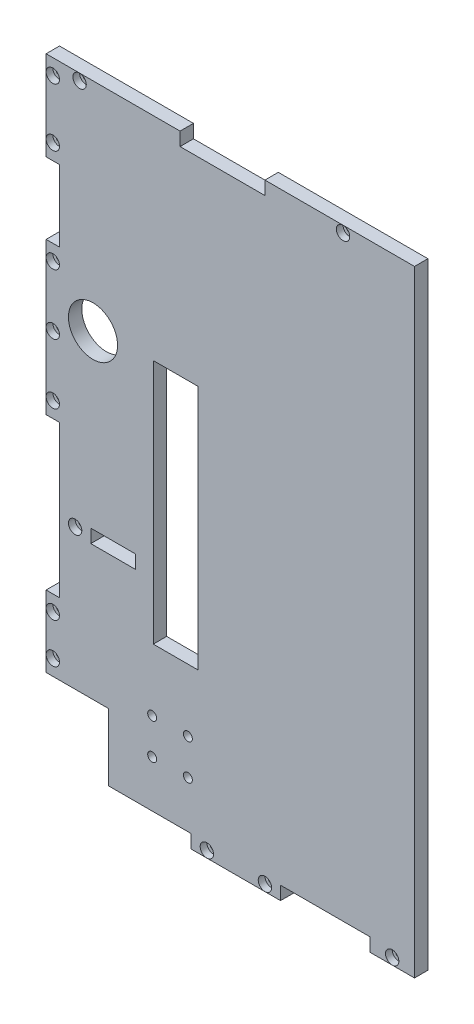
SolidWorks part; units mm, degrees
ref_plane "Plan de face" through (0, 0, 0) normal (0, 0, 1) x (1, 0, 0)
ref_plane "Plan de dessus" through (0, 0, 0) normal (0, 1, 0) x (1, 0, 0)
ref_plane "Plan de droite" through (0, 0, 0) normal (1, 0, 0) x (0, 0, -1)
sketch "Esquisse1" plane through (0, 0, 0) normal (0, 0, 1) x (1, 0, 0)
  line L1 (0, 0) -> (-165, 0)
  line L2 (0, 0) -> (0, 276)
  line L3 (0, 276) -> (-165, 276)
  line L4 (-165, 0) -> (-165, 276)
  dimension "D1" = 276
  dimension "D2" = 165
extrude "Boss.-Extru.1" add sketch "Esquisse1" along normal blind 6
sketch "Esquisse2" plane through (0, 0, 6) normal (0, 0, 1) x (1, 0, 0)
  line L8 (0, 276) -> (-165, 276) construction
  line L9 (-165, 0) -> (0, 0) construction
  line L10 (-105, 276) -> (-67, 276)
  line L11 (-105, 276) -> (-105, 270)
  line L12 (-105, 270) -> (-67, 270)
  line L13 (-165, 276) -> (-165, 0) construction
  line L14 (-165, 236) -> (-159, 236)
  line L15 (-165, 236) -> (-165, 204)
  line L16 (-165, 204) -> (-159, 204)
  line L17 (-159, 236) -> (-159, 204)
  line L19 (-165, 136) -> (-159, 136)
  line L20 (-165, 136) -> (-165, 68)
  line L21 (-165, 68) -> (-159, 68)
  line L22 (-159, 136) -> (-159, 68)
  line L23 (-137, 36) -> (-137, 6)
  line L24 (-165, 0) -> (-165, 36)
  line L25 (-165, 36) -> (-137, 36)
  line L26 (-100, 0) -> (-165, 0)
  line L27 (-20, 0) -> (-60, 0)
  line L28 (-20, 0) -> (-20, 6)
  line L29 (-20, 6) -> (-60, 6)
  line L30 (-60, 0) -> (-60, 6)
  line L31 (0, 0) -> (0, 276) construction
  line L33 (-100, 0) -> (-100, 6)
  line L34 (-100, 6) -> (-137, 6)
  line L35 (-67, 276) -> (-67, 270)
  dimension "D1" = 6
  dimension "D2" = 6
  dimension "D3" = 68
  dimension "D4" = 32
  dimension "D5" = 40
  dimension "D6" = 68
  dimension "D7" = 36
  dimension "D8" = 28
  dimension "D9" = 6
  dimension "D10" = 40
  dimension "D11" = 6
  dimension "D12" = 40
  dimension "D13" = 20
  dimension "D14" = 38
  dimension "D15" = 60
  dimension "D16" = 6
extrude "exterieur" cut sketch "Esquisse2" against normal blind 10
sketch "Esquisse3" plane through (0, 0, 6) normal (0, 0, 1) x (1, 0, 0)
  line L0 (-165, 204) -> (-159, 204) construction
  line L1 (-145, 102) -> (-125, 102)
  line L2 (-145, 102) -> (-145, 96)
  line L3 (-145, 96) -> (-125, 96)
  line L4 (-125, 102) -> (-125, 96)
  line L5 (-165, 204) -> (-165, 136) construction
  line L6 (-165, 68) -> (-165, 36) construction
  line L8 (-100, 0) -> (-60, 0) construction
  circle A0 centre (-144, 178.92) radius 11
  dimension "D1" = 22
  dimension "D2" = 20
  dimension "D4" = 21
  dimension "D3" = 6
  dimension "D5" = 25.08
  dimension "D6" = 20
  dimension "D7" = 102
extrude "Enlèv. mat.-Extru.2" cut sketch "Esquisse3" against normal through all
sketch "Esquisse4" plane through (0, 0, 6) normal (0, 0, 1) x (1, 0, 0)
  line L0 (-105, 270) -> (-67, 270) construction
  line L1 (-145, 96) -> (-125, 96) construction
  line L2 (-105, 276) -> (-105, 270) construction
  line L3 (-67, 270) -> (-67, 276) construction
  line L4 (-165, 204) -> (-159, 204) construction
  line L5 (-159, 136) -> (-165, 136) construction
  line L6 (-165, 68) -> (-159, 68) construction
  line L7 (-137, 36) -> (-165, 36) construction
  line L8 (-100, 0) -> (-100, 6) construction
  line L9 (-60, 6) -> (-60, 0) construction
  line L10 (-100, 0) -> (-60, 0) construction
  line L11 (-165, 68) -> (-165, 36) construction
  line L12 (-165, 204) -> (-165, 136) construction
  line L13 (-20, 0) -> (0, 0) construction
  line L14 (-20, 0) -> (-20, 6) construction
  line L15 (-145, 102) -> (-145, 96) construction
  line L17 (-159, 236) -> (-165, 236) construction
  line L18 (-105, 276) -> (-165, 276) construction
  line L19 (-165, 276) -> (-165, 236) construction
  circle A0 centre (-32, 273) radius 1.5
  circle A1 centre (-150, 273) radius 1.5
  circle A2 centre (-162, 197) radius 1.5
  circle A3 centre (-162, 170) radius 1.5
  circle A4 centre (-162, 143) radius 1.5
  circle A5 centre (-162, 61) radius 1.5
  circle A6 centre (-162, 43) radius 1.5
  circle A7 centre (-93, 3) radius 1.5
  circle A8 centre (-67, 3) radius 1.5
  circle A9 centre (-10, 3) radius 1.5
  circle A10 centre (-152, 99) radius 1.5
  circle A11 centre (-162, 243) radius 1.5
  circle A12 centre (-101.5, 43) radius 1.005
  circle A13 centre (-117.5, 43) radius 1.005
  circle A14 centre (-101.5, 27) radius 1.005
  circle A15 centre (-117.5, 27) radius 1.005
  circle A16 centre (-162, 269) radius 1.5
  point P28 (-162, 204)
  point P45 (-165, 170)
  point P46 (-10, 0)
  point P49 (-20, 3)
  dimension "D1" = 3
  dimension "D2" = 3
  dimension "D3" = 3
  dimension "D4" = 45
  dimension "D5" = 3
  dimension "D6" = 35
  dimension "D7" = 3
  dimension "D8" = 7
  dimension "D9" = 3
  dimension "D10" = 34
  dimension "D11" = 3
  dimension "D12" = 7
  dimension "D13" = 3
  dimension "D14" = 7
  dimension "D15" = 3
  dimension "D16" = 7
  dimension "D17" = 3
  dimension "D18" = 3
  dimension "D19" = 7
  dimension "D20" = 7
  dimension "D21" = 3
  dimension "D22" = 3
  dimension "D23" = 3
  dimension "D24" = 3
  dimension "D25" = 3
  dimension "D26" = 3
  dimension "D27" = 3
  dimension "D28" = 3
  dimension "D29" = 3
  dimension "D30" = 10
  dimension "D31" = 3
  dimension "D32" = 3
  dimension "D33" = 3
  dimension "D34" = 7
  dimension "D35" = 7
  dimension "D36" = 3
  dimension "D37" = 2.01
  dimension "D38" = 2.01
  dimension "D39" = 2.01
  dimension "D40" = 2.01
  dimension "D41" = 7
  dimension "D42" = 3
  dimension "D43" = 3
extrude "Enlèv. mat.-Extru.3" cut sketch "Esquisse4" against normal through all
sketch "Esquisse5" plane through (0, 0, 6) normal (0, 0, 1) x (1, 0, 0)
  circle A0 centre (-150, 273) radius 2.995
  circle A1 centre (-32, 273) radius 2.995
  circle A2 centre (-162, 197) radius 2.995
  circle A3 centre (-162, 170) radius 2.995
  circle A4 centre (-162, 143) radius 2.995
  circle A5 centre (-162, 61) radius 2.995
  circle A6 centre (-162, 43) radius 2.995
  circle A7 centre (-93, 3) radius 2.995
  circle A8 centre (-67, 3) radius 2.995
  circle A9 centre (-10, 3) radius 2.995
  circle A10 centre (-152, 99) radius 3
  circle A11 centre (-117.5, 43) radius 2
  circle A12 centre (-101.5, 43) radius 2
  circle A13 centre (-117.5, 27) radius 2
  circle A14 centre (-101.5, 27) radius 2
  circle A15 centre (-162, 269) radius 2.995
  circle A17 centre (-162, 243) radius 2.995
  dimension "D1" = 5.99
  dimension "D2" = 5.99
  dimension "D3" = 5.99
  dimension "D4" = 5.99
  dimension "D5" = 5.99
  dimension "D6" = 5.99
  dimension "D7" = 5.99
  dimension "D8" = 5.99
  dimension "D9" = 5.99
  dimension "D10" = 5.99
  dimension "D11" = 6
  dimension "D12" = 4
  dimension "D13" = 4
  dimension "D14" = 4
  dimension "D15" = 4
  dimension "D16" = 5.99
  dimension "D17" = 5.99
extrude "Enlèv. mat.-Extru.4" cut sketch "Esquisse5" against normal blind 3
sketch "Esquisse6" plane through (0, 0, 6) normal (0, 0, 1) x (1, 0, 0)
  line L0 (-165, 204) -> (-165, 136) construction
  line L1 (-117, 181) -> (-97, 181)
  line L2 (-117, 181) -> (-117, 71)
  line L3 (-117, 71) -> (-97, 71)
  line L4 (-97, 181) -> (-97, 71)
  line L5 (-100, 0) -> (-60, 0) construction
  dimension "D1" = 20
  dimension "D2" = 48
  dimension "D3" = 71
  dimension "D4" = 110
extrude "Enlèv. mat.-Extru.5" cut sketch "Esquisse6" against normal through all
